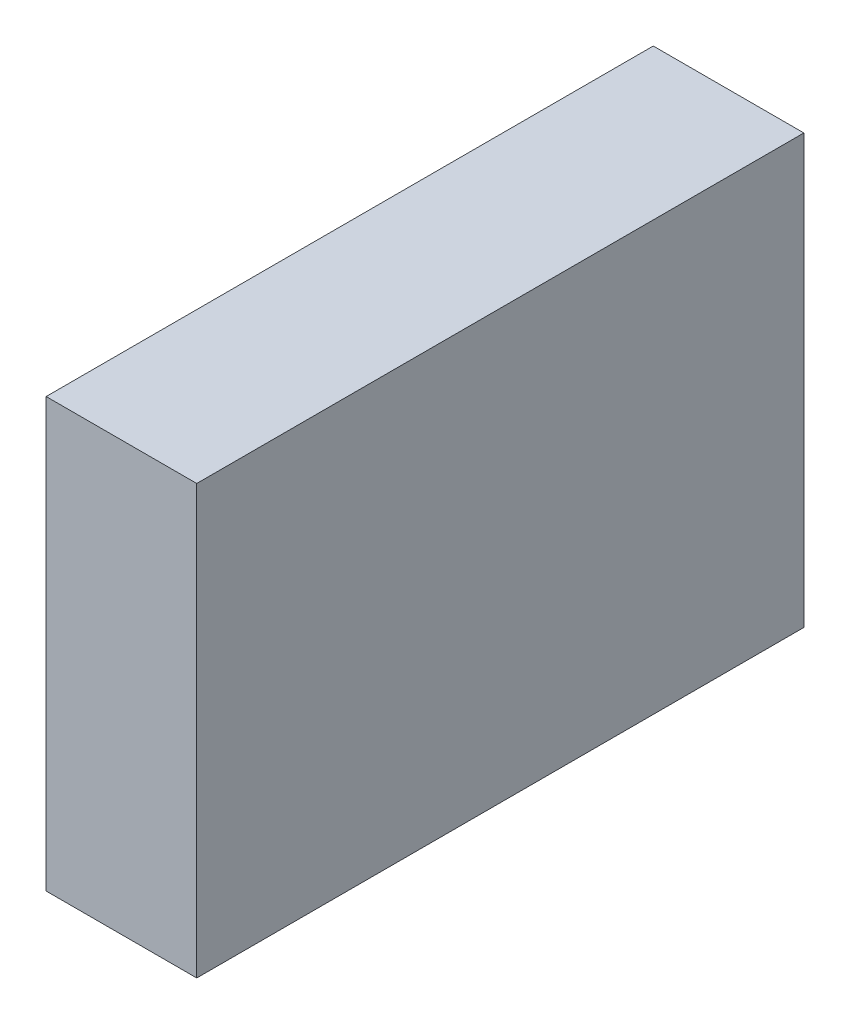
SolidWorks part; units mm, degrees
ref_plane "Front Plane" through (0, 0, 0) normal (0, 0, 1) x (1, 0, 0)
ref_plane "Top Plane" through (0, 0, 0) normal (0, 1, 0) x (1, 0, 0)
ref_plane "Right Plane" through (0, 0, 0) normal (1, 0, 0) x (0, 0, -1)
sketch "Sketch1" plane through (0, 0, 0) normal (1, 0, 0) x (0, 0, -1)
  line L0 (-2, 43.5) -> (62.5, 43.5)
  line L1 (0, 0) -> (60.5, 0) construction
  line L2 (0, 0) -> (0, 41.5) construction
  line L3 (0, 41.5) -> (60.5, 41.5) construction
  line L4 (60.5, 0) -> (60.5, 41.5) construction
  line L5 (62.5, -2) -> (62.5, 43.5)
  line L6 (-2, -2) -> (62.5, -2)
  line L7 (-2, -2) -> (-2, 43.5)
  dimension "D1" = 41.5
  dimension "D2" = 60.5
  dimension "D3" = 2
extrude "Boss-Extrude1" add sketch "Sketch1" along normal blind 2
sketch "Sketch2" plane through (0, 0, 0) normal (-1, 0, 0) x (0, 0, 1)
  line L0 (-60.5, 41.5) -> (-60.5, 0)
  line L1 (-62.5, 43.5) -> (2, 43.5)
  line L2 (-62.5, 43.5) -> (-62.5, -2)
  line L3 (-62.5, -2) -> (2, -2)
  line L4 (2, 43.5) -> (2, -2)
  line L5 (-60.5, 0) -> (-32.5, 0)
  line L6 (0, 41.5) -> (0, 0)
  line L7 (-60.5, 41.5) -> (-32.5, 41.5)
  line L8 (-28, 41.5) -> (0, 41.5)
  line L10 (-32.5, 41.5) -> (-32.5, 0)
  line L12 (-28, 41.5) -> (-28, 0)
  line L13 (-60.5, 41.5) -> (0, 41.5) construction
  line L14 (-28, 0) -> (0, 0)
  line L15 (-60.5, 0) -> (0, 0) construction
  dimension "D2" = 28
  dimension "D3" = 28
  dimension "D1" = 2
extrude "Boss-Extrude2" add sketch "Sketch2" along normal blind 14
sketch "Sketch3" plane through (0, -2, 0) normal (0, 1, 0) x (1, 0, 0)
  line L0 (-14, -2) -> (-14, 62.5) construction
  line L1 (2, -2) -> (-14, -2) construction
  circle A0 centre (-14, 14) radius 14
  dimension "D1" = 16
  dimension "D2" = 28
extrude "Cut-Extrude1" cut sketch "Sketch3" along normal up to next
sketch "Sketch4" plane through (-14, 0, 0) normal (-1, 0, 0) x (0, 0, 1)
  line L0 (-29, 40.5) -> (-29, 1)
  line L1 (-31, 40) -> (-29.5, 40) construction
  line L2 (-31, 40) -> (-31, 1.5) construction
  line L3 (-31, 1.5) -> (-29.5, 1.5) construction
  line L4 (-29.5, 40) -> (-29.5, 1.5) construction
  line L5 (-32.5, 0) -> (-32.5, 41.5) construction
  line L6 (-28, 41.5) -> (-28, 0) construction
  line L7 (-28, 0) -> (0, 0) construction
  line L8 (-32.5, 41.5) -> (-60.5, 41.5) construction
  line L9 (-31.5, 1) -> (-29, 1)
  line L10 (-31.5, 40.5) -> (-31.5, 1)
  line L11 (-31.5, 40.5) -> (-29, 40.5)
  dimension "D1" = 1.5
  dimension "D2" = 1.5
  dimension "D3" = 1.5
  dimension "D4" = 1.5
  dimension "D5" = 0.5
extrude "Cut-Extrude2" cut sketch "Sketch4" against normal blind 5.5 contours L0 L9 L10 L11
sketch "Sketch5" plane through (0, 0, 0) normal (-1, 0, 0) x (0, 0, 1)
  line L1 (-32.5, 41.5) -> (-60.5, 41.5)
  line L2 (-32.5, 41.5) -> (-32.5, 0)
  line L3 (-32.5, 0) -> (-60.5, 0)
  line L4 (-60.5, 41.5) -> (-60.5, 0)
extrude "Boss-Extrude3" add sketch "Sketch5" along normal blind 10.16
sketch "Sketch6" plane through (0, 0, -62.5) normal (0, 0, -1) x (-1, 0, 0)
  line L0 (14, 43.5) -> (14, -2) construction
  line L1 (-2, -2) -> (14, -2) construction
  circle A0 centre (11.968, 10.7) radius 1.2
  circle A1 centre (11.968, 19.6803) radius 1.2
  dimension "D1" = 8.9803
  dimension "D2" = 2.4
  dimension "D3" = 2.4
  dimension "D4" = 2.032
  dimension "D5" = 12.7
extrude "Boss-Extrude4" add sketch "Sketch6" along normal blind 5.08
